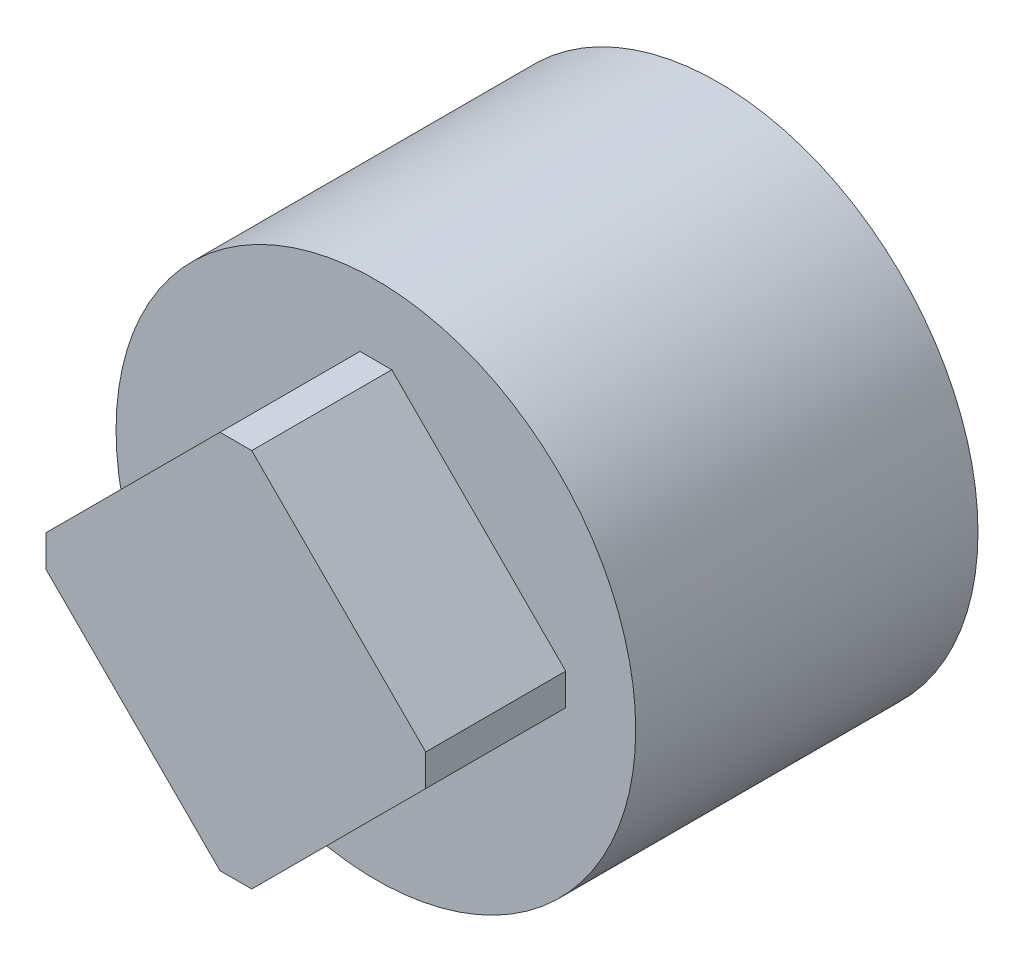
SolidWorks part; units mm, degrees
ref_plane "Front Plane" through (0, 0, 0) normal (0, 0, 1) x (1, 0, 0)
ref_plane "Top Plane" through (0, 0, 0) normal (0, 1, 0) x (1, 0, 0)
ref_plane "Right Plane" through (0, 0, 0) normal (1, 0, 0) x (0, 0, -1)
sketch "Sketch1" plane through (0, 0, 0) normal (0, 0, 1) x (1, 0, 0)
  circle A0 centre (0, 0) radius 16.7
extrude "Replaceable drive insert body" add sketch "Sketch1" along normal blind 22 from offset 1
sketch "Sketch2" plane through (0, 0, 0) normal (0, 0, 1) x (1, 0, 0)
  line L0 (1.02, 12.2029) -> (-1.02, 12.2029)
  line L1 (-1.02, 12.2029) -> (-12.2029, 1.02)
  line L2 (-12.2029, 1.02) -> (-12.2029, -1.02)
  line L3 (-12.2029, -1.02) -> (-1.02, -12.2029)
  line L4 (-1.02, -12.2029) -> (1.02, -12.2029)
  line L5 (1.02, -12.2029) -> (12.2029, -1.02)
  line L6 (12.2029, -1.02) -> (12.2029, 1.02)
  line L7 (12.2029, 1.02) -> (1.02, 12.2029)
extrude "Common positive drive tang" add sketch "Sketch2" along normal blind 9 from offset 23
sketch "Sketch3" plane through (0, 0, 0) normal (0, 0, 1) x (1, 0, 0)
  line L0 (1.02, 9.0209) -> (-1.02, 9.0209)
  line L1 (-1.02, 9.0209) -> (-9.0209, 1.02)
  line L2 (-9.0209, 1.02) -> (-9.0209, -1.02)
  line L3 (-9.0209, -1.02) -> (-1.02, -9.0209)
  line L4 (-1.02, -9.0209) -> (1.02, -9.0209)
  line L5 (1.02, -9.0209) -> (9.0209, -1.02)
  line L6 (9.0209, -1.02) -> (9.0209, 1.02)
  line L7 (9.0209, 1.02) -> (1.02, 9.0209)
extrude "Valve stem socket, nominal flats 14 mm" cut sketch "Sketch3" along normal blind 19.1 from offset 1
sketch "Sketch4" plane through (0, 0, 0) normal (0, 0, 1) x (1, 0, 0)
  circle A0 centre (0, 0) radius 10.2
extrude "Stem corner clearance at entry" cut sketch "Sketch4" along normal blind 1.1 from offset 1
